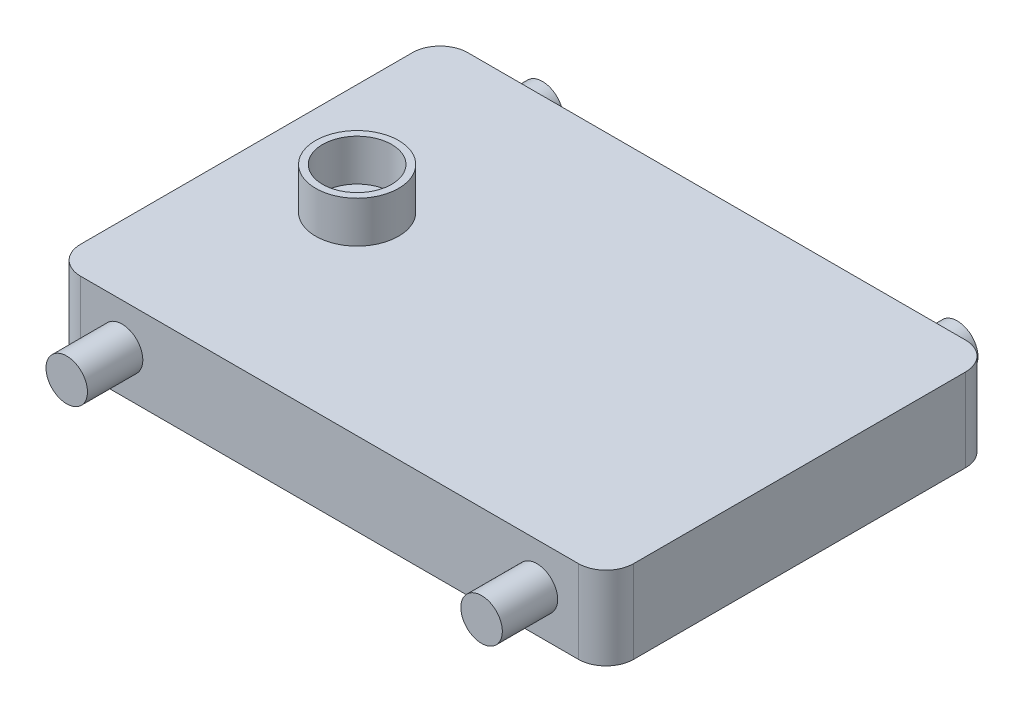
SolidWorks part; units mm, degrees
ref_plane "Front Plane" through (0, 0, 0) normal (0, 0, 1) x (1, 0, 0)
ref_plane "Top Plane" through (0, 0, 0) normal (0, 1, 0) x (1, 0, 0)
ref_plane "Right Plane" through (0, 0, 0) normal (1, 0, 0) x (0, 0, -1)
sketch "Sketch1" plane through (0, 0, 0) normal (0, 1, 0) x (1, 0, 0)
  line L1 (-100, -70) -> (100, -70)
  line L2 (-100, -70) -> (-100, 70)
  line L3 (-100, 70) -> (100, 70)
  line L4 (100, -70) -> (100, 70)
  line L5 (-100, -70) -> (100, 70) construction
  line L6 (-100, 70) -> (100, -70) construction
  point P0 (0, 0)
  dimension "D1" = 200
  dimension "D2" = 140
extrude "Boss-Extrude1" add sketch "Sketch1" along normal blind 30
fillet "Fillet1" radius 10 4 edges at (-100, 15, -70) (-100, 15, 70) (100, 15, 70) (100, 15, -70)
sketch "Sketch2" plane through (0, 0, 70) normal (0, 0, 1) x (1, 0, 0)
  line L0 (-90, 0) -> (90, 0) construction
  line L1 (-90, 30) -> (-90, 0) construction
  line L2 (0, 0) -> (0, 30) construction
  line L3 (-90, 30) -> (90, 30) construction
  circle A0 centre (-75, 15) radius 7.5
  circle A1 centre (75, 15) radius 7.5
  dimension "D1" = 15
  dimension "D2" = 15
  dimension "D3" = 15
extrude "Boss-Extrude2" add sketch "Sketch2" along normal blind 20
sketch "Sketch4" plane through (0, 0, -70) normal (0, 0, -1) x (-1, 0, 0)
  line L0 (-90, 0) -> (90, 0) construction
  line L1 (-90, 30) -> (-90, 0) construction
  line L2 (0, 0) -> (0, 30) construction
  line L3 (-90, 30) -> (90, 30) construction
  circle A0 centre (-75, 15) radius 7.5
  circle A1 centre (75, 15) radius 7.5
  dimension "D1" = 15
  dimension "D2" = 15
  dimension "D3" = 15
extrude "Boss-Extrude3" add sketch "Sketch4" along normal blind 12
sketch "Sketch6" plane through (0, 0, 0) normal (0, -1, 0) x (1, 0, 0)
  line L0 (90, -70) -> (-90, -70) construction
  circle A0 centre (-60, 0) radius 12.5
  circle A1 centre (-60, 0) radius 15
  dimension "D1" = 25
  dimension "D4" = 30
  dimension "D2" = 70
  dimension "D3" = 60
extrude "Boss-Extrude4" add sketch "Sketch6" against normal blind 45
